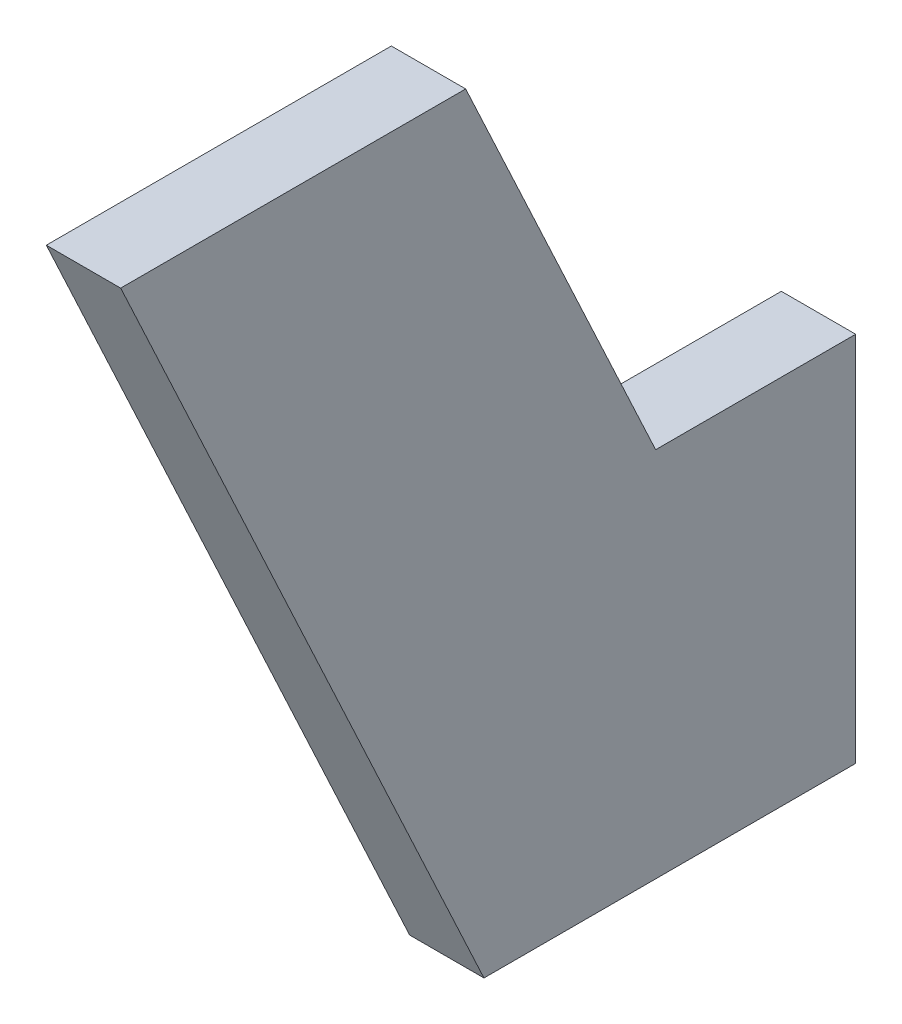
SolidWorks part; units mm, degrees
ref_plane "前视基准面" through (0, 0, 0) normal (0, 0, 1) x (1, 0, 0)
ref_plane "上视基准面" through (0, 0, 0) normal (0, 1, 0) x (1, 0, 0)
ref_plane "右视基准面" through (0, 0, 0) normal (1, 0, 0) x (0, 0, -1)
sketch "草图1" plane through (0, 0, 0) normal (0, 0, 1) x (1, 0, 0)
  line L0 (0, 40) -> (0, -40) construction
  line L1 (-8, 40) -> (8, 40)
  line L2 (-8, 40) -> (-8, -40)
  line L3 (-8, -40) -> (8, -40)
  line L4 (8, 40) -> (8, -40)
  line L5 (-8, 40) -> (8, -40) construction
  line L6 (-8, -40) -> (8, 40) construction
  line L7 (0, 40) -> (0, 32) construction
  line L8 (0, -40) -> (0, -32) construction
  circle A0 centre (0, 32) radius 2.25
  circle A1 centre (0, 0) radius 2.25
  circle A2 centre (0, -32) radius 2.25
  point P0 (0, 0)
extrude "凸台-拉伸1" add sketch "草图1" along normal blind 80
sketch "草图2" plane through (8, 0, 0) normal (1, 0, 0) x (0, 0, -1)
  line L0 (-80, -40) -> (-100.2155, -40) construction
  line L1 (-80, -40) -> (-100.3726, 3.6893) construction
  line L2 (-80, -40) -> (-100.3726, 3.6893)
  line L3 (-100.3726, 3.6893) -> (-158.1987, 127.6976)
  line L4 (-158.1987, 127.6976) -> (-83.9448, 127.6976)
  line L5 (-83.9448, 127.6976) -> (-43.0507, 40)
  line L6 (-80, 40) -> (0, 40) construction
  line L7 (-43.0507, 40) -> (-80, -40)
  dimension "D1" = 65
extrude "凸台-拉伸2" add sketch "草图2" against normal blind 16
